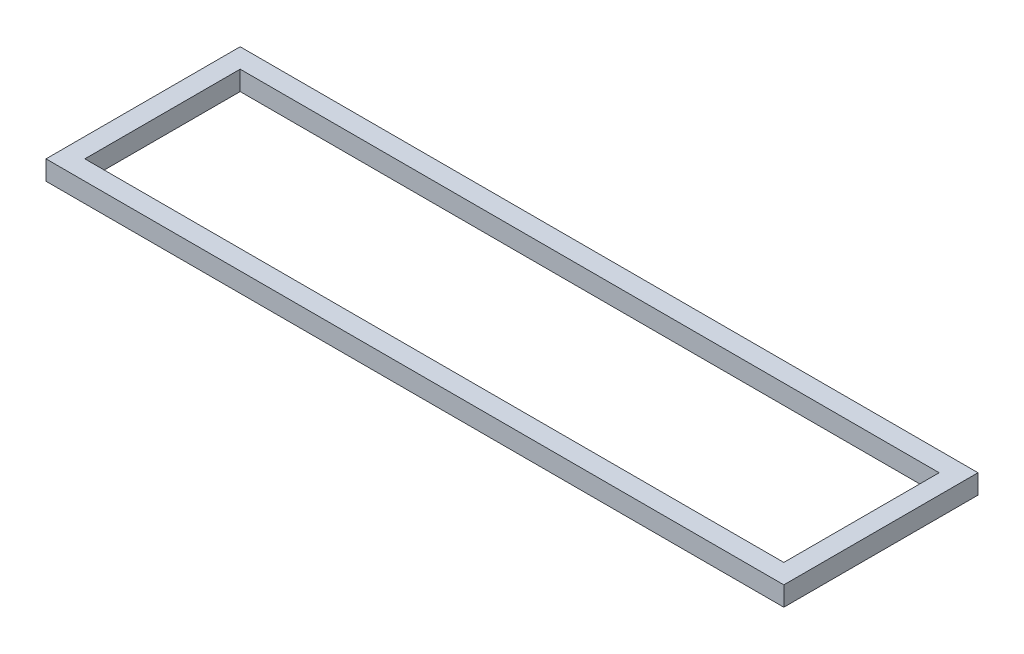
SolidWorks part; units mm, degrees
ref_plane "Front Plane" through (0, 0, 0) normal (0, 0, 1) x (1, 0, 0)
ref_plane "Top Plane" through (0, 0, 0) normal (0, 1, 0) x (1, 0, 0)
ref_plane "Right Plane" through (0, 0, 0) normal (1, 0, 0) x (0, 0, -1)
sketch "Sketch1" plane through (0, 0, 0) normal (0, 1, 0) x (1, 0, 0)
  line L1 (0, 0) -> (120.65, 0)
  line L2 (0, 0) -> (0, 31.75)
  line L3 (0, 31.75) -> (120.65, 31.75)
  line L4 (120.65, 0) -> (120.65, 31.75)
  dimension "D1" = 120.65
  dimension "D2" = 31.75
extrude "Boss-Extrude1" add sketch "Sketch1" along normal blind 3.175
sketch "Sketch4" plane through (0, 3.175, 0) normal (0, 1, 0) x (1, 0, 0)
  line L0 (0, 31.75) -> (0, 0) construction
  line L1 (3.175, 28.575) -> (117.475, 28.575)
  line L2 (3.175, 28.575) -> (3.175, 3.175)
  line L3 (3.175, 3.175) -> (117.475, 3.175)
  line L4 (117.475, 28.575) -> (117.475, 3.175)
  line L5 (120.65, 31.75) -> (0, 31.75) construction
  dimension "D1" = 114.3
  dimension "D2" = 3.175
  dimension "D3" = 25.4
  dimension "D4" = 3.175
extrude "Cut-Extrude1" cut sketch "Sketch4" against normal blind 5.08
